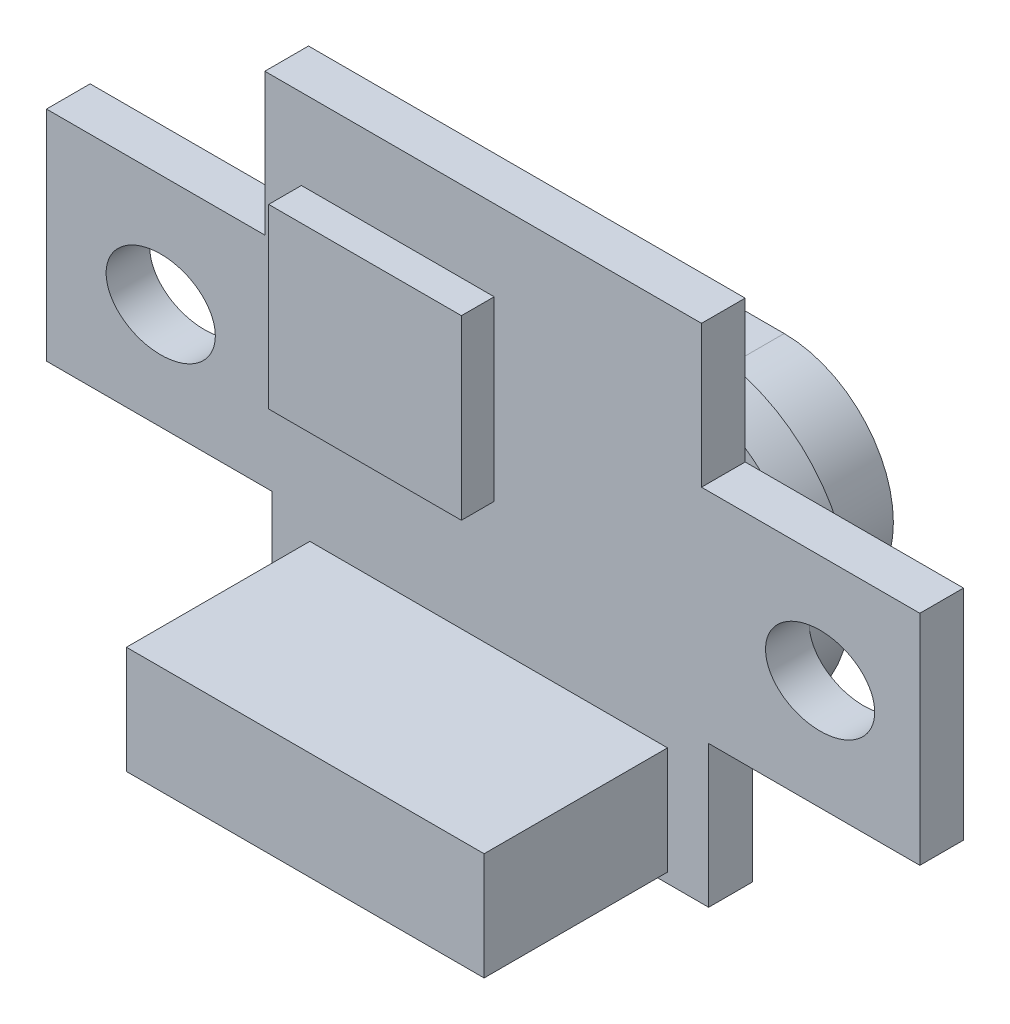
SolidWorks part; units mm, degrees
ref_plane "Front Plane" through (0, 0, 0) normal (0, 0, 1) x (1, 0, 0)
ref_plane "Top Plane" through (0, 0, 0) normal (0, 1, 0) x (1, 0, 0)
ref_plane "Right Plane" through (0, 0, 0) normal (1, 0, 0) x (0, 0, -1)
sketch "Sketch1" plane through (0, 0, 0) normal (0, 0, 1) x (1, 0, 0)
  line L5 (-2.7804, 3.5277) -> (7.2196, 3.5277)
  line L6 (7.2196, 3.5277) -> (7.2196, 0.2777)
  line L11 (7.2196, 0.2777) -> (12.2196, 0.2777)
  line L12 (12.2196, 0.2777) -> (12.2196, -4.7223)
  line L16 (12.2196, -4.7223) -> (7.3833, -4.7223)
  line L17 (7.3833, -4.7223) -> (7.3833, -7.9723)
  line L18 (7.3833, -7.9723) -> (-2.6167, -7.9723)
  line L19 (-2.6167, -7.9723) -> (-2.6167, -4.7223)
  line L20 (-2.6167, -4.7223) -> (-7.7804, -4.7223)
  line L21 (-7.7804, -4.7223) -> (-7.7804, 0.2777)
  line L22 (-7.7804, 0.2777) -> (-2.7804, 0.2777)
  line L23 (-2.7804, 0.2777) -> (-2.7804, 3.5277)
  dimension "D1" = 10
  dimension "D2" = 10
  dimension "D3" = 3.25
  dimension "D4" = 3.25
  dimension "D5" = 3.25
  dimension "D6" = 3.25
  dimension "D7" = 11.5
  dimension "D8" = 20
  dimension "D9" = 5
  dimension "D10" = 5
extrude "Boss-Extrude1" add sketch "Sketch1" along normal blind 1
sketch "Sketch2" plane through (0, 0, 1) normal (0, 0, 1) x (1, 0, 0)
  ellipse E0 centre (9.9358, -2.2006) end of major axis (11.1858, -2.2006) minor radius 1
  ellipse E1 centre (-5.1642, -2.2894) end of major axis (-3.9142, -2.2894) minor radius 1
  dimension "D1" = 15.1
extrude "Cut-Extrude1" cut sketch "Sketch2" against normal through all
sketch "Sketch5" plane through (0, 0, 0) normal (0, 0, -1) x (-1, 0, 0)
  line L0 (-5.2855, -2.2427) -> (0.5145, -2.2427) construction
  line L1 (-5.2855, 1.1573) -> (0.5145, 1.1573)
  line L2 (-5.2855, -5.6427) -> (0.5145, -5.6427)
  arc A0 (-5.2855, 1.1573) -> (-5.2855, -5.6427) centre (-5.2855, -2.2427) ccw
  arc A1 (0.5145, -5.6427) -> (0.5145, 1.1573) centre (0.5145, -2.2427) ccw
  point P2 (-2.3855, -2.2427)
  dimension "D1" = 6.8
  dimension "D2" = 5.8
extrude "Boss-Extrude2" add sketch "Sketch5" along normal blind 0.95
sketch "Sketch6" plane through (0, 0, -0.95) normal (0, 0, -1) x (-1, 0, 0)
  line L0 (-5.0634, -2.2772) -> (0.5056, -2.2772) construction
  line L1 (-5.0634, 0.2228) -> (0.5056, 0.2228)
  line L2 (-5.0634, -4.7772) -> (0.5056, -4.7772)
  arc A0 (-5.0634, 0.2228) -> (-5.0634, -4.7772) centre (-5.0634, -2.2772) ccw
  arc A1 (0.5056, -4.7772) -> (0.5056, 0.2228) centre (0.5056, -2.2772) ccw
  point P2 (-2.2789, -2.2772)
  dimension "D1" = 5
extrude "Boss-Extrude3" add sketch "Sketch6" along normal blind 2.1
sketch "Sketch7" plane through (0, 0, 1) normal (0, 0, 1) x (1, 0, 0)
  line L1 (-1.7498, -5.2808) -> (6.4411, -5.2808)
  line L2 (-1.7498, -5.2808) -> (-1.7498, -7.7451)
  line L3 (-1.7498, -7.7451) -> (6.4411, -7.7451)
  line L4 (6.4411, -5.2808) -> (6.4411, -7.7451)
  line L5 (-1.7498, -5.2808) -> (6.4411, -7.7451) construction
  line L6 (-1.7498, -7.7451) -> (6.4411, -5.2808) construction
  point P0 (2.3456, -6.5129)
extrude "Boss-Extrude4" add sketch "Sketch7" along normal blind 4.2
sketch "Sketch8" plane through (0, 0, 1) normal (0, 0, 1) x (1, 0, 0)
  line L1 (-1.9423, 1.6805) -> (2.4714, 1.6805)
  line L2 (-1.9423, 1.6805) -> (-1.9423, -2.3778)
  line L3 (-1.9423, -2.3778) -> (2.4714, -2.3778)
  line L4 (2.4714, 1.6805) -> (2.4714, -2.3778)
  line L5 (-1.9423, 1.6805) -> (2.4714, -2.3778) construction
  line L6 (-1.9423, -2.3778) -> (2.4714, 1.6805) construction
  point P0 (0.2645, -0.3487)
extrude "Boss-Extrude5" add sketch "Sketch8" along normal blind 0.75
